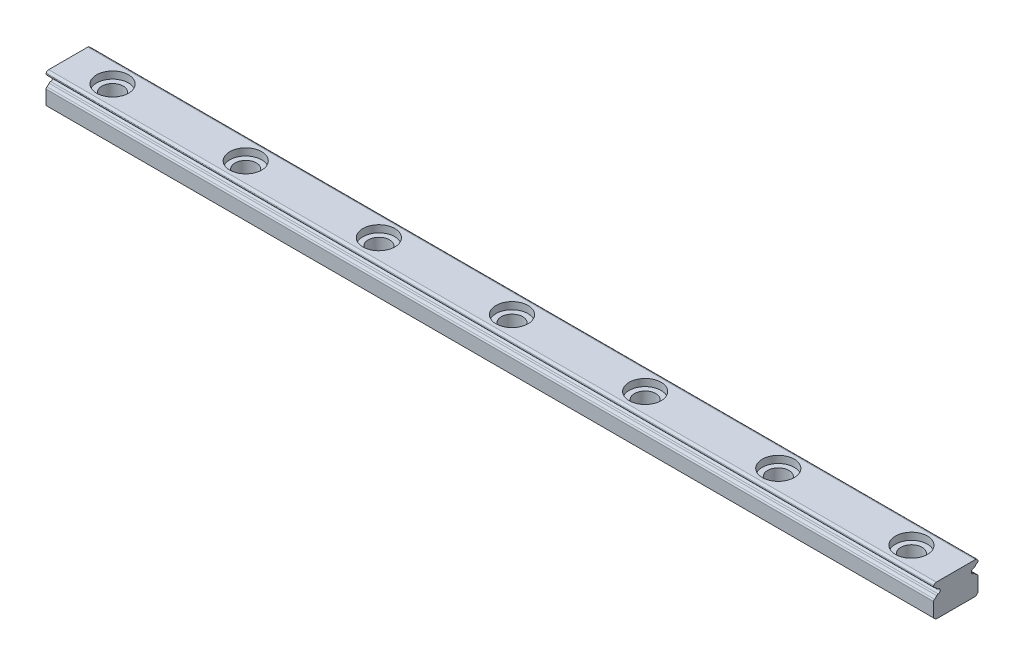
SolidWorks part; units mm, degrees
ref_plane "前视基准面" through (0, 0, 0) normal (0, 0, 1) x (1, 0, 0)
ref_plane "上视基准面" through (0, 0, 0) normal (0, 1, 0) x (1, 0, 0)
ref_plane "右视基准面" through (0, 0, 0) normal (1, 0, 0) x (0, 0, -1)
sketch "草图1" plane through (0, 0, 0) normal (1, 0, 0) x (0, 0, -1)
  line L1 (2.5, -1.8) -> (-2.5, -1.8)
  line L2 (2.5, -1.8) -> (2.5, 1.8)
  line L3 (2.5, 1.8) -> (-2.5, 1.8)
  line L4 (-2.5, -1.8) -> (-2.5, 1.8)
  line L5 (2.5, -1.8) -> (-2.5, 1.8) construction
  line L6 (2.5, 1.8) -> (-2.5, -1.8) construction
  point P0 (0, 0)
  dimension "D1" = 5
  dimension "D2" = 3.6
extrude "凸台-拉伸1" add sketch "草图1" along normal mid plane 100
sketch "草图2" plane through (50, 0, 0) normal (1, 0, 0) x (0, 0, -1)
  line L0 (2.5, 1.4) -> (2.5, 0.184)
  line L1 (-2.5, 1.8) -> (-2.5, -1.8) construction
  line L2 (-2.1, 1.042) -> (-2, 1.042)
  line L3 (-2, 0.542) -> (-2.1, 0.542)
  line L4 (-2.5, 1.4) -> (-2.5, 0.184)
  line L5 (-2, 0.792) -> (-2.5, 0.792) construction
  line L6 (2.5, 1.8) -> (-2.5, 1.8) construction
  line L7 (2.5, 1.8) -> (-2.5, 1.8) construction
  line L8 (0, 0) -> (0, 1.2431) construction
  line L9 (2, 0.792) -> (2.5, 0.792) construction
  line L12 (2, 0.542) -> (2.1, 0.542)
  line L13 (2.1, 1.042) -> (2, 1.042)
  arc A0 (-2, 1.042) -> (-2, 0.542) centre (-2, 0.792) cw
  arc A1 (2, 1.042) -> (2, 0.542) centre (2, 0.792) ccw
  arc A2 (-2.5, 0.184) -> (-2.1, 0.542) centre (-2.684, 0.792) ccw
  arc A3 (-2.1, 1.042) -> (-2.5, 1.4) centre (-2.684, 0.792) ccw
  arc A4 (2.1, 1.042) -> (2.5, 1.4) centre (2.684, 0.792) cw
  arc A5 (2.5, 0.184) -> (2.1, 0.542) centre (2.684, 0.792) cw
  dimension "D1" = 0.5
  dimension "D5" = 4.2
  dimension "D2" = 1.008
  dimension "D3" = 0.4
  dimension "D4" = 4
extrude "切除-拉伸1" cut sketch "草图2" against normal through all
sketch "草图3" plane through (0, 1.8, 0) normal (0, 1, 0) x (1, 0, 0)
  line L0 (-50, 2.5) -> (-50, -2.5) construction
  line L1 (0, 0) -> (-2.9109, 0) construction
  circle A0 centre (-45, 0) radius 1.8
  dimension "D2" = 3.5999
  dimension "D1" = 5
extrude "切除-拉伸2" cut sketch "草图3" against normal blind 0.8
sketch "草图4" plane through (0, 1, 0) normal (0, 1, 0) x (1, 0, 0)
  circle A0 centre (-45, 0) radius 1.2
  dimension "D1" = 2.4
extrude "切除-拉伸3" cut sketch "草图4" against normal through all
fillet "圆角1" radius 0.3 2 edges at (0, 1.8, -2.5) (0, 1.8, 2.5)
fillet "圆角2" radius 0.2 8 edges at (0, 1.4, -2.5) (0, 1.042, -2.1) (0, 0.542, -2.1) (0, 0.184, -2.5) (0, 0.184, 2.5) (0, 1.4, 2.5) (0, 1.042, 2.1) (0, 0.542, 2.1)
chamfer "倒角1" distance 0.25 angle 45 2 edges at (0, -1.8, 2.5) (0, -1.8, -2.5)
pattern_linear "阵列(线性)1" count 7 spacing 15 along (1, 0, 0) of "切除-拉伸2", "切除-拉伸3"
